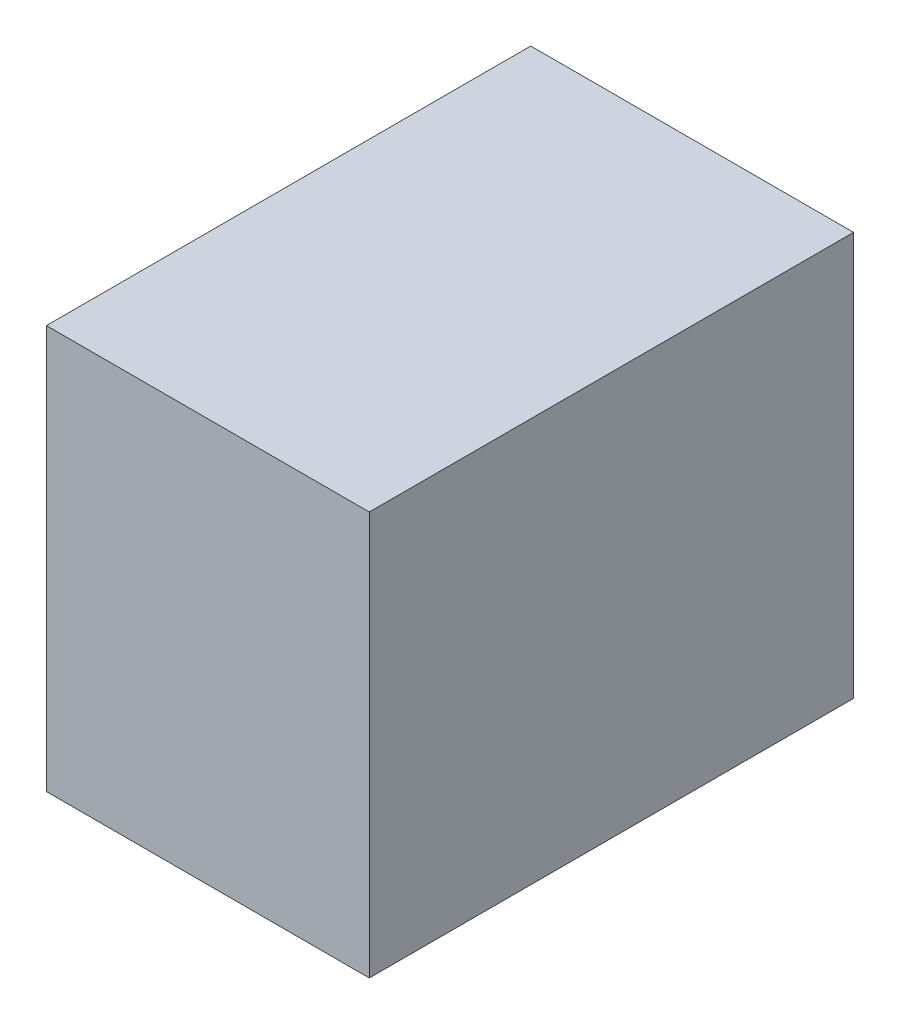
SolidWorks part; units mm, degrees
ref_plane "Front Plane" through (0, 0, 0) normal (0, 0, 1) x (1, 0, 0)
ref_plane "Top Plane" through (0, 0, 0) normal (0, 1, 0) x (1, 0, 0)
ref_plane "Right Plane" through (0, 0, 0) normal (1, 0, 0) x (0, 0, -1)
other "Configuration Table"
sketch "Sketch1" plane through (0, 0, 0) normal (0, 0, 1) x (1, 0, 0)
  line L1 (270, 320) -> (310, 320)
  line L2 (270, 320) -> (270, 370)
  line L3 (270, 370) -> (310, 370)
  line L4 (310, 320) -> (310, 370)
extrude "PACK_vakum_selenoid_kapak_1" add sketch "Sketch1" against normal blind 60 from offset 620 separate body
